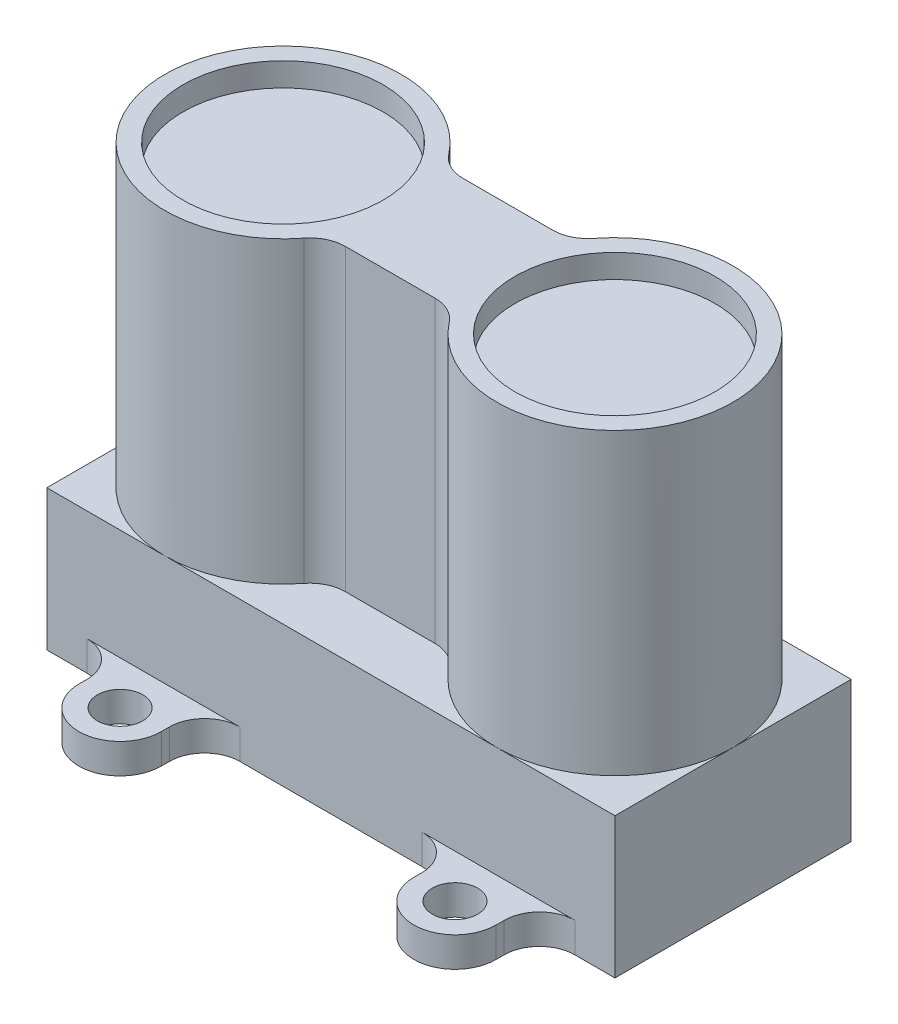
SolidWorks part; units mm, degrees
ref_plane "Front Plane" through (0, 0, 0) normal (0, 0, 1) x (1, 0, 0)
ref_plane "Top Plane" through (0, 0, 0) normal (0, 1, 0) x (1, 0, 0)
ref_plane "Right Plane" through (0, 0, 0) normal (1, 0, 0) x (0, 0, -1)
sketch "Sketch1" plane through (0, 0, 0) normal (0, 1, 0) x (1, 0, 0)
  line L0 (-30.2328, 0) -> (33.1758, 0) construction
  line L1 (0, 22.4293) -> (0, -20.3335) construction
  line L2 (-24.13, 10.033) -> (-20.724, 10.033)
  line L3 (-24.13, 10.033) -> (-24.13, -10.033)
  line L4 (-24.13, -10.033) -> (-20.724, -10.033)
  line L5 (24.13, 10.033) -> (24.13, -10.033)
  line L6 (-24.13, 10.033) -> (24.13, -10.033) construction
  line L7 (-24.13, -10.033) -> (24.13, 10.033) construction
  line L8 (-17.724, 13.716) -> (-17.724, 13.033)
  line L9 (-10.724, 13.716) -> (-10.724, 13.033)
  line L10 (-17.724, -13.716) -> (-17.724, -13.033)
  line L11 (-10.724, -13.716) -> (-10.724, -13.033)
  line L12 (17.724, 13.716) -> (17.724, 13.033)
  line L13 (10.724, 13.716) -> (10.724, 13.033)
  line L14 (10.724, -13.716) -> (10.724, -13.033)
  line L15 (17.724, -13.716) -> (17.724, -13.033)
  line L16 (-7.724, 10.033) -> (7.724, 10.033)
  line L17 (-7.724, -10.033) -> (7.724, -10.033)
  line L18 (20.724, -10.033) -> (24.13, -10.033)
  line L19 (20.724, 10.033) -> (24.13, 10.033)
  circle A0 centre (-14.224, 13.716) radius 1.925
  circle A1 centre (-14.224, -13.716) radius 1.925
  circle A2 centre (14.224, -13.716) radius 1.925
  circle A3 centre (14.224, 13.716) radius 1.925
  arc A4 (-10.724, 13.716) -> (-17.724, 13.716) centre (-14.224, 13.716) ccw
  arc A5 (-10.724, -13.716) -> (-17.724, -13.716) centre (-14.224, -13.716) cw
  arc A6 (10.724, 13.716) -> (17.724, 13.716) centre (14.224, 13.716) cw
  arc A7 (10.724, -13.716) -> (17.724, -13.716) centre (14.224, -13.716) ccw
  arc A8 (-17.724, -13.033) -> (-20.724, -10.033) centre (-20.724, -13.033) ccw
  arc A9 (-10.724, -13.033) -> (-7.724, -10.033) centre (-7.724, -13.033) cw
  arc A10 (10.724, -13.033) -> (7.724, -10.033) centre (7.724, -13.033) ccw
  arc A11 (17.724, -13.033) -> (20.724, -10.033) centre (20.724, -13.033) cw
  arc A12 (17.724, 13.033) -> (20.724, 10.033) centre (20.724, 13.033) ccw
  arc A13 (10.724, 13.033) -> (7.724, 10.033) centre (7.724, 13.033) cw
  arc A14 (-10.724, 13.033) -> (-7.724, 10.033) centre (-7.724, 13.033) ccw
  arc A15 (-17.724, 13.033) -> (-20.724, 10.033) centre (-20.724, 13.033) cw
  point P3 (0, 0)
  point P32 (-17.724, -10.033)
  point P39 (-10.724, -10.033)
  point P42 (10.724, -10.033)
  point P45 (17.724, -10.033)
  point P48 (17.724, 10.033)
  point P51 (10.724, 10.033)
  point P54 (-10.724, 10.033)
  point P57 (-17.724, 10.033)
  dimension "D5" = 3.85
  dimension "D6" = 7
  dimension "D7" = 3
  dimension "D1" = 20.066
  dimension "D2" = 48.26
  dimension "D3" = 27.432
  dimension "D4" = 28.448
extrude "Boss-Extrude1" add sketch "Sketch1" along normal blind 2.54
sketch "Sketch2" plane through (0, 2.54, 0) normal (0, 1, 0) x (1, 0, 0)
  line L1 (-24.13, 10.033) -> (24.13, 10.033)
  line L2 (-24.13, 10.033) -> (-24.13, -10.033)
  line L3 (-24.13, -10.033) -> (24.13, -10.033)
  line L4 (24.13, 10.033) -> (24.13, -10.033)
extrude "Boss-Extrude2" add sketch "Sketch2" along normal blind 9.398
sketch "Sketch3" plane through (0, 11.938, 0) normal (0, 1, 0) x (1, 0, 0)
  line L0 (0, 12.9626) -> (0, -17.512) construction
  line L1 (-27.3197, 0) -> (29.8573, 0) construction
  line L2 (-3.8082, 5) -> (3.8082, 5)
  line L3 (-3.8082, -5) -> (3.8082, -5)
  arc A0 (-6.1765, 6.1585) -> (-6.1765, -6.1585) centre (-14.097, 0) ccw
  arc A1 (6.1765, 6.1585) -> (6.1765, -6.1585) centre (14.097, 0) cw
  arc A2 (-3.8082, -5) -> (-6.1765, -6.1585) centre (-3.8082, -8) ccw
  arc A3 (3.8082, -5) -> (6.1765, -6.1585) centre (3.8082, -8) cw
  arc A4 (3.8082, 5) -> (6.1765, 6.1585) centre (3.8082, 8) ccw
  arc A5 (-3.8082, 5) -> (-6.1765, 6.1585) centre (-3.8082, 8) cw
  point P13 (-5.3987, -5)
  point P16 (5.3987, -5)
  point P19 (5.3987, 5)
  point P22 (-5.3987, 5)
  dimension "D2" = 3
  dimension "D1" = 10
extrude "Boss-Extrude3" add sketch "Sketch3" along normal blind 25.4
sketch "Sketch4" plane through (0, 37.338, 0) normal (0, 1, 0) x (1, 0, 0)
  line L0 (-24.13, 0) -> (24.13, 0) construction
  line L1 (0, 12.4166) -> (0, -15.2216) construction
  circle A0 centre (14.097, 0) radius 8.5
  circle A1 centre (-14.097, 0) radius 8.5
  dimension "D1" = 17
extrude "Cut-Extrude1" cut sketch "Sketch4" against normal blind 2
